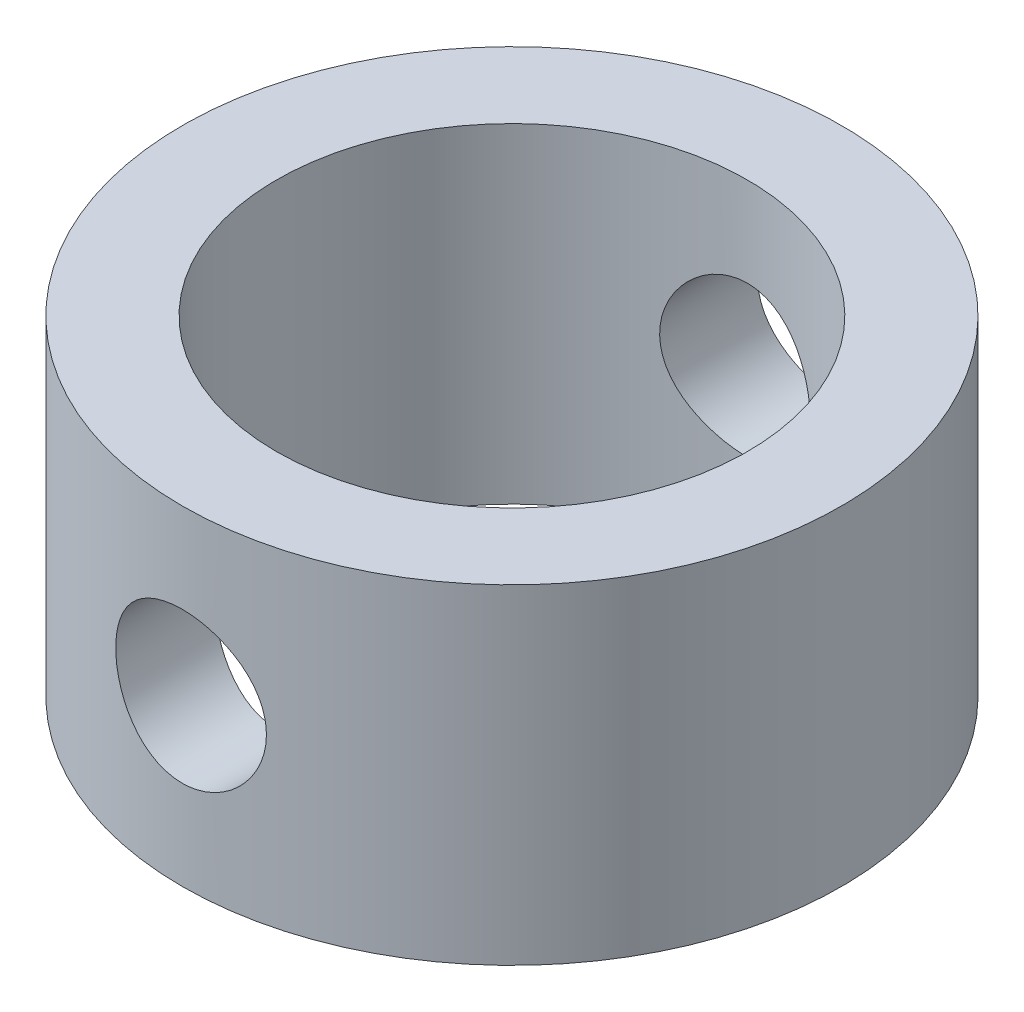
SolidWorks part; units mm, degrees
ref_plane "Plano frontal" through (0, 0, 0) normal (0, 0, 1) x (1, 0, 0)
ref_plane "Plano superior" through (0, 0, 0) normal (0, 1, 0) x (1, 0, 0)
ref_plane "Plano direito" through (0, 0, 0) normal (1, 0, 0) x (0, 0, -1)
sketch "Esboço1" plane through (0, 0, 0) normal (0, 1, 0) x (1, 0, 0)
  circle A0 centre (0, 0) radius 5
  circle A1 centre (0, 0) radius 7
  dimension "D1" = 10
  dimension "D2" = 14
extrude "Ressalto-extrusão1" add sketch "Esboço1" along normal blind 7
sketch "Esboço2" plane through (0, 0, 0) normal (0, 0, 1) x (1, 0, 0)
  line L0 (0, 7) -> (0, 0) construction
  line L1 (7, 7) -> (-7, 7) construction
  circle A0 centre (0, 3.5) radius 1.6
  dimension "D1" = 3.2
extrude "Corte-extrusão1" cut sketch "Esboço2" against normal through all both and the other way through all
